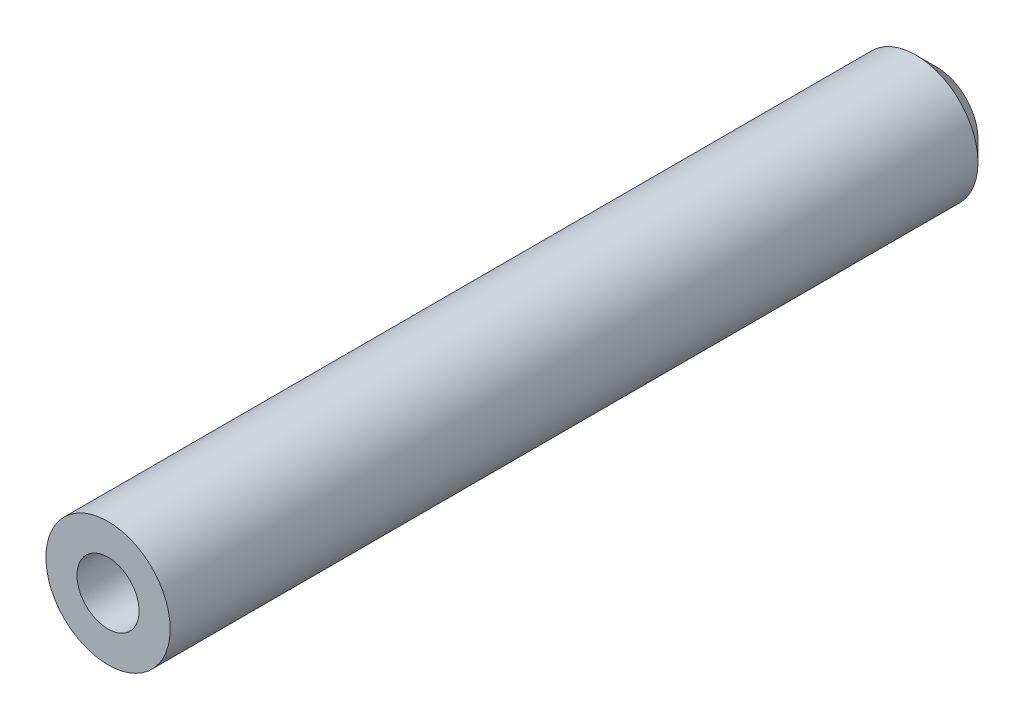
SolidWorks part; units mm, degrees
ref_plane "Front Plane" through (0, 0, 0) normal (0, 0, 1) x (1, 0, 0)
ref_plane "Top Plane" through (0, 0, 0) normal (0, 1, 0) x (1, 0, 0)
ref_plane "Right Plane" through (0, 0, 0) normal (1, 0, 0) x (0, 0, -1)
sketch "Sketch1" plane through (0, 0, 0) normal (0, 1, 0) x (1, 0, 0)
  line L0 (0, 0) -> (0, 20.7766) construction
  line L1 (-3, 39) -> (-2, 40)
  line L2 (-2, 40) -> (-1.5, 40)
  line L3 (-1.5, 40) -> (-1.5, 0)
  line L4 (-1.5, 0) -> (-3, 0)
  line L5 (-3, 0) -> (-3, 39)
  point P5 (-1.9043, 18.7017)
  dimension "D1" = 3
  dimension "D2" = 6
  dimension "D3" = 135
  dimension "D4" = 0.5
  dimension "D5" = 40
revolve "Revolve1" add sketch "Sketch1" angle 360 about L0
